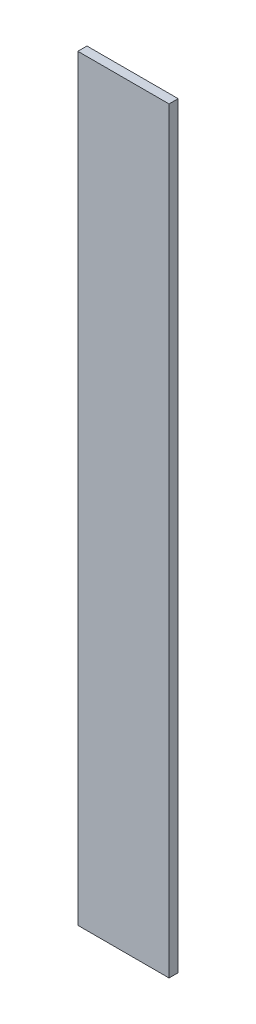
SolidWorks part; units mm, degrees
ref_plane "Płaszczyzna przednia" through (0, 0, 0) normal (0, 0, 1) x (1, 0, 0)
ref_plane "Płaszczyzna górna" through (0, 0, 0) normal (0, 1, 0) x (1, 0, 0)
ref_plane "Płaszczyzna prawa" through (0, 0, 0) normal (1, 0, 0) x (0, 0, -1)
sketch "Szkic1" plane through (0, 0, 0) normal (0, 0, 1) x (1, 0, 0)
  line L1 (0, 0) -> (10, 0)
  line L2 (0, 0) -> (0, 83)
  line L3 (0, 83) -> (10, 83)
  line L4 (10, 0) -> (10, 83)
  point P5 (0, 0)
  point P6 (0, 0)
  point P7 (0, 0)
extrude "Dodanie-wyciągnięcie1" add sketch "Szkic1" along normal blind 1
